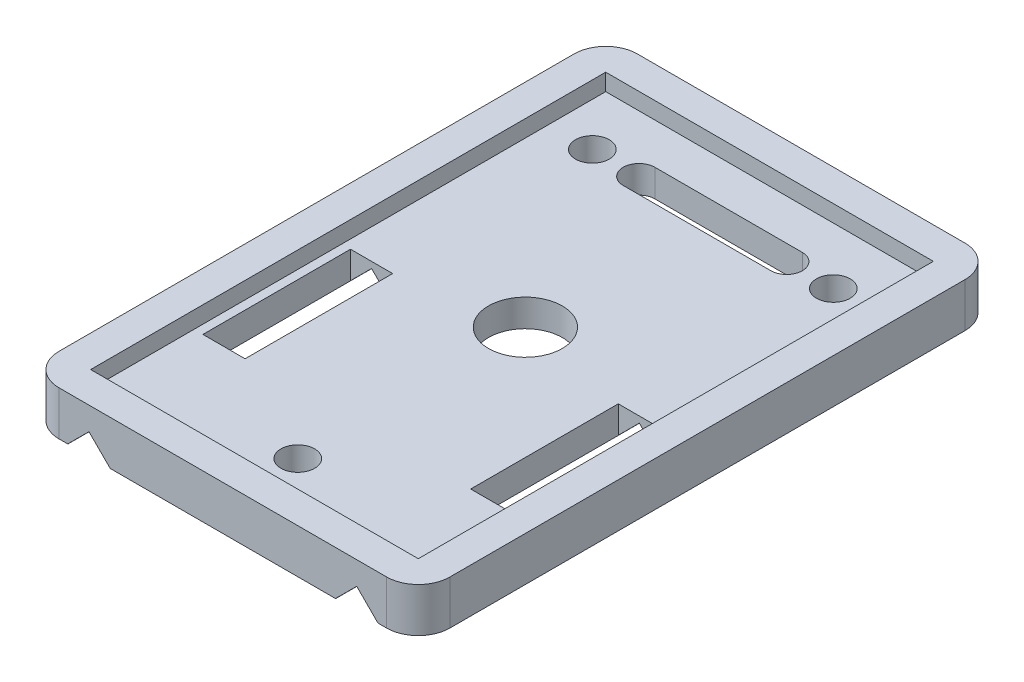
SolidWorks part; units mm, degrees
ref_plane "Front Plane" through (0, 0, 0) normal (0, 0, 1) x (1, 0, 0)
ref_plane "Top Plane" through (0, 0, 0) normal (0, 1, 0) x (1, 0, 0)
ref_plane "Right Plane" through (0, 0, 0) normal (1, 0, 0) x (0, 0, -1)
sketch "Sketch1" plane through (0, 0, 0) normal (0, 1, 0) x (1, 0, 0)
  line L1 (0, 0) -> (30.48, 0) construction
  line L2 (0, 0) -> (0, 48.26) construction
  line L3 (0, 48.26) -> (30.48, 48.26) construction
  line L4 (30.48, 0) -> (30.48, 48.26) construction
  line L8 (-0.3, -0.3) -> (-0.3, 48.56)
  line L9 (-0.3, 48.56) -> (30.78, 48.56)
  line L10 (30.78, -0.3) -> (30.78, 48.56)
  line L11 (-0.3, -0.3) -> (30.78, -0.3)
  line L12 (-3.3, -0.3) -> (-3.3, 48.56)
  line L13 (-0.3, 51.56) -> (30.78, 51.56)
  line L14 (33.78, -0.3) -> (33.78, 48.56)
  line L15 (-0.3, -3.3) -> (30.78, -3.3)
  line L16 (-3.3, -3.3) -> (-3.3, 51.56) construction
  line L17 (-3.3, -3.3) -> (33.78, -3.3) construction
  line L18 (33.78, -3.3) -> (33.78, 51.56) construction
  line L19 (-3.3, 51.56) -> (33.78, 51.56) construction
  arc A3 (-3.3, -0.3) -> (-0.3, -3.3) centre (-0.3, -0.3) ccw
  arc A4 (30.78, -3.3) -> (33.78, -0.3) centre (30.78, -0.3) ccw
  arc A5 (33.78, 48.56) -> (30.78, 51.56) centre (30.78, 48.56) ccw
  arc A6 (-0.3, 51.56) -> (-3.3, 48.56) centre (-0.3, 48.56) ccw
  dimension "D4" = 3
  dimension "D5" = 3
  dimension "D2" = 48.26
  dimension "D3" = 30.48
  dimension "D1" = 3
  dimension "D7" = 0.3
sketch "Sketch2" plane through (0, 0, 0) normal (0, 1, 0) x (1, 0, 0)
  circle A0 centre (3.81, 43.18) radius 1.6
  circle A1 centre (26.67, 43.18) radius 1.6
  circle A2 centre (15.24, 3.81) radius 1.6
  dimension "D7" = 3.2
  dimension "D8" = 3.2
  dimension "D9" = 3.2
  dimension "D1" = 3.81
  dimension "D2" = 15.24
  dimension "D3" = 43.18
  dimension "D4" = 3.81
  dimension "D5" = 43.18
  dimension "D6" = 26.67
sketch "Sketch3" plane through (0, 0, 0) normal (0, 1, 0) x (1, 0, 0)
  line L0 (15.24, 3.81) -> (15.24, 45.3871) construction
  line L10 (4.54, 9.51) -> (0.54, 9.51)
  line L11 (4.54, 9.51) -> (4.54, 23.51)
  line L12 (4.54, 23.51) -> (0.54, 23.51)
  line L13 (0.54, 9.51) -> (0.54, 23.51)
  line L14 (4.54, 9.51) -> (0.54, 23.51) construction
  line L15 (4.54, 23.51) -> (0.54, 9.51) construction
  line L16 (25.94, 23.51) -> (29.94, 9.51) construction
  line L17 (25.94, 9.51) -> (29.94, 23.51) construction
  line L18 (25.94, 23.51) -> (29.94, 23.51)
  line L19 (29.94, 9.51) -> (29.94, 23.51)
  line L20 (25.94, 9.51) -> (29.94, 9.51)
  line L21 (25.94, 9.51) -> (25.94, 23.51)
  point P0 (2.54, 16.51)
  dimension "D1" = 2.54
  dimension "D2" = 16.51
  dimension "D3" = 14
  dimension "D4" = 4
extrude "Boss-Extrude1" add sketch "Sketch1" along normal blind 4.2 contours L12 A6 L13 A5 L14 A4 L15 A3
extrude "Cut-Extrude4" cut sketch "Sketch2" against normal through all and the other way through all contours A0 | A1 | A2
extrude "Cut-Extrude5" cut sketch "Sketch3" along normal through all contours L12 L13 L10 L11 | L18 L19 L20 L21
sketch "Sketch6" plane through (0, 4.2, 0) normal (0, 1, 0) x (1, 0, 0)
  line L4 (-0.3, 48.56) -> (-0.3, -0.3)
  line L5 (30.78, 48.56) -> (-0.3, 48.56)
  line L6 (30.78, -0.3) -> (30.78, 48.56)
  line L7 (-0.3, -0.3) -> (30.78, -0.3)
  line L8 (-0.3, 48.56) -> (-0.3, -0.3)
  line L9 (30.78, 48.56) -> (-0.3, 48.56)
  line L10 (30.78, -0.3) -> (30.78, 48.56)
  line L11 (-0.3, -0.3) -> (30.78, -0.3)
  line L12 (-3.3, 48.56) -> (-3.3, -0.3)
  line L13 (-0.3, -3.3) -> (30.78, -3.3)
  line L14 (33.78, -0.3) -> (33.78, 48.56)
  line L15 (30.78, 51.56) -> (-0.3, 51.56)
  line L16 (-3.3, 48.56) -> (-3.3, -0.3)
  line L17 (-0.3, -3.3) -> (30.78, -3.3)
  line L18 (33.78, -0.3) -> (33.78, 48.56)
  line L19 (30.78, 51.56) -> (-0.3, 51.56)
  arc A4 (-3.3, -0.3) -> (-0.3, -3.3) centre (-0.3, -0.3) ccw
  arc A5 (30.78, -3.3) -> (33.78, -0.3) centre (30.78, -0.3) ccw
  arc A6 (33.78, 48.56) -> (30.78, 51.56) centre (30.78, 48.56) ccw
  arc A7 (-0.3, 51.56) -> (-3.3, 48.56) centre (-0.3, 48.56) ccw
  arc A8 (-3.3, -0.3) -> (-0.3, -3.3) centre (-0.3, -0.3) ccw
  arc A9 (30.78, -3.3) -> (33.78, -0.3) centre (30.78, -0.3) ccw
  arc A10 (33.78, 48.56) -> (30.78, 51.56) centre (30.78, 48.56) ccw
  arc A11 (-0.3, 51.56) -> (-3.3, 48.56) centre (-0.3, 48.56) ccw
  dimension "D1" = 0
  dimension "D2" = 0
extrude "Cut-Extrude6" cut sketch "Sketch6" against normal blind 1.6 contours L8 L11 L10 L9
sketch "Sketch8" plane through (0, 0, 3.3) normal (0, 0, 1) x (1, 0, 0)
  line L0 (27.94, 2.0142) -> (29.9542, 0)
  line L1 (27.94, 2.0142) -> (25.9258, 0)
  line L2 (27.94, 0.6) -> (27.94, 2.3185) construction
  line L3 (2.54, 0.6) -> (2.54, 2.544) construction
  line L4 (29.94, 2.6) -> (25.94, 2.6)
  line L5 (25.94, 2.6) -> (25.94, 0)
  line L6 (25.94, 0) -> (29.94, 0)
  line L7 (29.94, 0) -> (29.94, 2.6)
  line L8 (29.94, 2.6) -> (25.94, 2.6)
  line L9 (25.94, 2.6) -> (25.94, 0)
  line L10 (25.94, 0) -> (29.94, 0)
  line L11 (29.94, 0) -> (29.94, 2.6)
  line L12 (4.54, 0) -> (4.54, 2.6)
  line L13 (4.54, 2.6) -> (0.54, 2.6)
  line L14 (0.54, 2.6) -> (0.54, 0)
  line L15 (0.54, 0) -> (4.54, 0)
  line L16 (4.54, 0) -> (4.54, 2.6)
  line L17 (4.54, 2.6) -> (0.54, 2.6)
  line L18 (0.54, 2.6) -> (0.54, 0)
  line L19 (0.54, 0) -> (4.54, 0)
  line L20 (2.54, 2.0142) -> (4.5542, 0)
  line L21 (2.54, 2.0142) -> (0.5258, 0)
  circle A0 centre (27.94, 0.6) radius 1
  circle A1 centre (2.54, 0.6) radius 1
  line M17 (-0.3, 0) -> (30.78, 0)
  dimension "D3" = 2
  dimension "D6" = 2
  dimension "D7" = 2
  dimension "D8" = 2
  dimension "D4" = 45
  dimension "D5" = 45
  dimension "D1" = 0
  dimension "D2" = 0
extrude "Cut-Extrude7" cut sketch "Sketch8" against normal blind 35 and the other way through all contours A1 L21 L18 M17 | A1 L20 L21 | A1 L19 | A1 L16 L20 M17 | A0 L11 L0 M17 | A0 L0 L1 | A0 L10 | A0 L1 L9 M17
sketch "Sketch9" plane through (0, 2.6, 0) normal (0, 1, 0) x (1, 0, 0)
  line L0 (8.24, 43.18) -> (22.24, 43.18) construction
  line L1 (8.24, 44.68) -> (22.24, 44.68)
  line L2 (8.24, 41.68) -> (22.24, 41.68)
  line L3 (3.81, 43.18) -> (26.67, 43.18) construction
  circle A0 centre (15.24, 25.4) radius 3.5
  arc A1 (8.24, 44.68) -> (8.24, 41.68) centre (8.24, 43.18) ccw
  arc A2 (22.24, 41.68) -> (22.24, 44.68) centre (22.24, 43.18) ccw
  point P4 (15.24, 43.18)
  dimension "D3" = 7
  dimension "D5" = 1.5
  dimension "D1" = 15.24
  dimension "D2" = 25.4
  dimension "D4" = 14
extrude "Cut-Extrude8" cut sketch "Sketch9" against normal through all both and the other way through all
